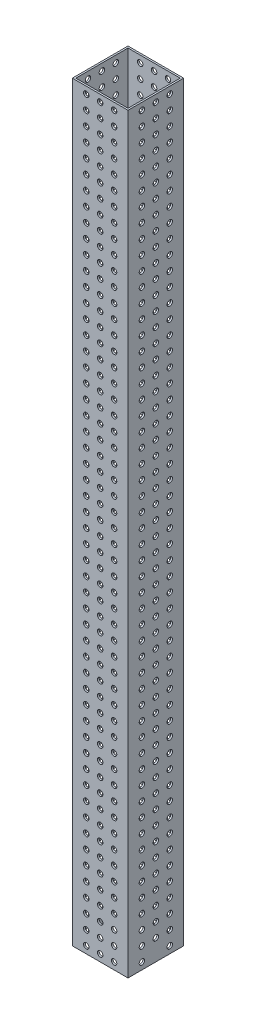
SolidWorks part; units mm, degrees
ref_plane "Front Plane" through (0, 0, 0) normal (0, 0, 1) x (1, 0, 0)
ref_plane "Top Plane" through (0, 0, 0) normal (0, 1, 0) x (1, 0, 0)
ref_plane "Right Plane" through (0, 0, 0) normal (1, 0, 0) x (0, 0, -1)
sketch "Sketch1" plane through (0, 0, 0) normal (0, 1, 0) x (1, 0, 0)
  line L1 (-25.4, 25.4) -> (25.4, 25.4)
  line L2 (-25.4, 25.4) -> (-25.4, -25.4)
  line L3 (-25.4, -25.4) -> (25.4, -25.4)
  line L4 (25.4, 25.4) -> (25.4, -25.4)
  line L5 (-25.4, 25.4) -> (25.4, -25.4) construction
  line L6 (-25.4, -25.4) -> (25.4, 25.4) construction
  line L7 (23.8125, 23.8125) -> (-23.8125, 23.8125)
  line L8 (23.8125, 23.8125) -> (23.8125, -23.8125)
  line L9 (23.8125, -23.8125) -> (-23.8125, -23.8125)
  line L10 (-23.8125, 23.8125) -> (-23.8125, -23.8125)
  line L11 (23.8125, 23.8125) -> (-23.8125, -23.8125) construction
  line L12 (23.8125, -23.8125) -> (-23.8125, 23.8125) construction
  point P0 (0, 0)
  point P6 (0, 0)
  dimension "D1" = 50.8
  dimension "D2" = 50.8
  dimension "D3" = 1.5875
  dimension "D4" = 1.5875
extrude "Boss-Extrude1" add sketch "Sketch1" along normal blind 685.8
sketch "Sketch2" plane through (0, 0, 25.4) normal (0, 0, 1) x (1, 0, 0)
  line L0 (0, 685.8) -> (0, 0) construction
  line L1 (-25.4, 685.8) -> (25.4, 685.8) construction
  line L2 (-25.4, 685.8) -> (-25.4, 0) construction
  line L3 (-6.35, -314.2) -> (-6.35, 49685.8) construction
  circle A0 centre (-12.7, 679.45) radius 2.4892
  circle A1 centre (-12.7, 666.75) radius 2.4892
  circle A2 centre (-12.7, 654.05) radius 2.4892
  circle A3 centre (-12.7, 641.35) radius 2.4892
  circle A4 centre (-12.7, 628.65) radius 2.4892
  circle A5 centre (-12.7, 615.95) radius 2.4892
  circle A6 centre (-12.7, 603.25) radius 2.4892
  circle A7 centre (-12.7, 590.55) radius 2.4892
  circle A8 centre (-12.7, 577.85) radius 2.4892
  circle A9 centre (-12.7, 565.15) radius 2.4892
  circle A10 centre (-12.7, 552.45) radius 2.4892
  circle A11 centre (-12.7, 539.75) radius 2.4892
  circle A12 centre (-12.7, 527.05) radius 2.4892
  circle A13 centre (-12.7, 514.35) radius 2.4892
  circle A14 centre (-12.7, 501.65) radius 2.4892
  circle A15 centre (-12.7, 488.95) radius 2.4892
  circle A16 centre (-12.7, 476.25) radius 2.4892
  circle A17 centre (-12.7, 463.55) radius 2.4892
  circle A18 centre (-12.7, 450.85) radius 2.4892
  circle A19 centre (-12.7, 438.15) radius 2.4892
  circle A20 centre (-12.7, 425.45) radius 2.4892
  circle A21 centre (-12.7, 412.75) radius 2.4892
  circle A22 centre (-12.7, 400.05) radius 2.4892
  circle A23 centre (-12.7, 387.35) radius 2.4892
  circle A24 centre (-12.7, 374.65) radius 2.4892
  circle A25 centre (-12.7, 361.95) radius 2.4892
  circle A26 centre (-12.7, 349.25) radius 2.4892
  circle A27 centre (-12.7, 336.55) radius 2.4892
  circle A28 centre (-12.7, 323.85) radius 2.4892
  circle A29 centre (-12.7, 311.15) radius 2.4892
  circle A30 centre (-12.7, 298.45) radius 2.4892
  circle A31 centre (-12.7, 285.75) radius 2.4892
  circle A32 centre (-12.7, 273.05) radius 2.4892
  circle A33 centre (-12.7, 260.35) radius 2.4892
  circle A34 centre (-12.7, 247.65) radius 2.4892
  circle A35 centre (-12.7, 234.95) radius 2.4892
  circle A36 centre (-12.7, 222.25) radius 2.4892
  circle A37 centre (-12.7, 209.55) radius 2.4892
  circle A38 centre (-12.7, 196.85) radius 2.4892
  circle A39 centre (-12.7, 184.15) radius 2.4892
  circle A40 centre (-12.7, 171.45) radius 2.4892
  circle A41 centre (-12.7, 158.75) radius 2.4892
  circle A42 centre (-12.7, 146.05) radius 2.4892
  circle A43 centre (-12.7, 133.35) radius 2.4892
  circle A44 centre (-12.7, 120.65) radius 2.4892
  circle A45 centre (-12.7, 107.95) radius 2.4892
  circle A46 centre (-12.7, 95.25) radius 2.4892
  circle A47 centre (-12.7, 82.55) radius 2.4892
  circle A48 centre (-12.7, 69.85) radius 2.4892
  circle A49 centre (-12.7, 57.15) radius 2.4892
  circle A50 centre (-12.7, 44.45) radius 2.4892
  circle A51 centre (-12.7, 31.75) radius 2.4892
  circle A52 centre (-12.7, 19.05) radius 2.4892
  circle A53 centre (-12.7, 6.35) radius 2.4892
  circle A54 centre (12.7, 6.35) radius 2.4892
  circle A55 centre (12.7, 19.05) radius 2.4892
  circle A56 centre (12.7, 31.75) radius 2.4892
  circle A57 centre (12.7, 44.45) radius 2.4892
  circle A58 centre (12.7, 57.15) radius 2.4892
  circle A59 centre (12.7, 69.85) radius 2.4892
  circle A60 centre (12.7, 82.55) radius 2.4892
  circle A61 centre (12.7, 95.25) radius 2.4892
  circle A62 centre (12.7, 107.95) radius 2.4892
  circle A63 centre (12.7, 120.65) radius 2.4892
  circle A64 centre (12.7, 133.35) radius 2.4892
  circle A65 centre (12.7, 146.05) radius 2.4892
  circle A66 centre (12.7, 158.75) radius 2.4892
  circle A67 centre (12.7, 171.45) radius 2.4892
  circle A68 centre (12.7, 184.15) radius 2.4892
  circle A69 centre (12.7, 196.85) radius 2.4892
  circle A70 centre (12.7, 209.55) radius 2.4892
  circle A71 centre (12.7, 222.25) radius 2.4892
  circle A72 centre (12.7, 234.95) radius 2.4892
  circle A73 centre (12.7, 247.65) radius 2.4892
  circle A74 centre (12.7, 260.35) radius 2.4892
  circle A75 centre (12.7, 273.05) radius 2.4892
  circle A76 centre (12.7, 285.75) radius 2.4892
  circle A77 centre (12.7, 298.45) radius 2.4892
  circle A78 centre (12.7, 311.15) radius 2.4892
  circle A79 centre (12.7, 323.85) radius 2.4892
  circle A80 centre (12.7, 336.55) radius 2.4892
  circle A81 centre (12.7, 374.65) radius 2.4892
  circle A82 centre (12.7, 361.95) radius 2.4892
  circle A83 centre (12.7, 349.25) radius 2.4892
  circle A84 centre (12.7, 387.35) radius 2.4892
  circle A85 centre (12.7, 400.05) radius 2.4892
  circle A86 centre (12.7, 412.75) radius 2.4892
  circle A87 centre (12.7, 425.45) radius 2.4892
  circle A88 centre (12.7, 438.15) radius 2.4892
  circle A89 centre (12.7, 450.85) radius 2.4892
  circle A90 centre (12.7, 463.55) radius 2.4892
  circle A91 centre (12.7, 476.25) radius 2.4892
  circle A92 centre (12.7, 488.95) radius 2.4892
  circle A93 centre (12.7, 501.65) radius 2.4892
  circle A94 centre (12.7, 514.35) radius 2.4892
  circle A95 centre (12.7, 527.05) radius 2.4892
  circle A96 centre (12.7, 539.75) radius 2.4892
  circle A97 centre (12.7, 552.45) radius 2.4892
  circle A98 centre (12.7, 565.15) radius 2.4892
  circle A99 centre (12.7, 577.85) radius 2.4892
  circle A100 centre (12.7, 590.55) radius 2.4892
  circle A101 centre (12.7, 603.25) radius 2.4892
  circle A102 centre (12.7, 615.95) radius 2.4892
  circle A103 centre (12.7, 628.65) radius 2.4892
  circle A104 centre (12.7, 641.35) radius 2.4892
  circle A105 centre (12.7, 654.05) radius 2.4892
  circle A106 centre (12.7, 666.75) radius 2.4892
  circle A107 centre (12.7, 679.45) radius 2.4892
  circle A108 centre (0, 6.35) radius 2.4892
  circle A109 centre (0, 19.05) radius 2.4892
  circle A110 centre (0, 31.75) radius 2.4892
  circle A111 centre (0, 44.45) radius 2.4892
  circle A112 centre (0, 57.15) radius 2.4892
  circle A113 centre (0, 69.85) radius 2.4892
  circle A114 centre (0, 82.55) radius 2.4892
  circle A115 centre (0, 95.25) radius 2.4892
  circle A116 centre (0, 107.95) radius 2.4892
  circle A117 centre (0, 120.65) radius 2.4892
  circle A118 centre (0, 133.35) radius 2.4892
  circle A119 centre (0, 146.05) radius 2.4892
  circle A120 centre (0, 158.75) radius 2.4892
  circle A121 centre (0, 171.45) radius 2.4892
  circle A122 centre (0, 184.15) radius 2.4892
  circle A123 centre (0, 196.85) radius 2.4892
  circle A124 centre (0, 209.55) radius 2.4892
  circle A125 centre (0, 222.25) radius 2.4892
  circle A126 centre (0, 234.95) radius 2.4892
  circle A127 centre (0, 247.65) radius 2.4892
  circle A128 centre (0, 260.35) radius 2.4892
  circle A129 centre (0, 273.05) radius 2.4892
  circle A130 centre (0, 285.75) radius 2.4892
  circle A131 centre (0, 298.45) radius 2.4892
  circle A132 centre (0, 311.15) radius 2.4892
  circle A133 centre (0, 323.85) radius 2.4892
  circle A134 centre (0, 336.55) radius 2.4892
  circle A135 centre (0, 349.25) radius 2.4892
  circle A136 centre (0, 361.95) radius 2.4892
  circle A137 centre (0, 374.65) radius 2.4892
  circle A138 centre (0, 387.35) radius 2.4892
  circle A139 centre (0, 400.05) radius 2.4892
  circle A140 centre (0, 412.75) radius 2.4892
  circle A141 centre (0, 425.45) radius 2.4892
  circle A142 centre (0, 438.15) radius 2.4892
  circle A143 centre (0, 450.85) radius 2.4892
  circle A144 centre (0, 463.55) radius 2.4892
  circle A145 centre (0, 476.25) radius 2.4892
  circle A146 centre (0, 488.95) radius 2.4892
  circle A147 centre (0, 501.65) radius 2.4892
  circle A148 centre (0, 514.35) radius 2.4892
  circle A149 centre (0, 527.05) radius 2.4892
  circle A150 centre (0, 539.75) radius 2.4892
  circle A151 centre (0, 552.45) radius 2.4892
  circle A152 centre (0, 565.15) radius 2.4892
  circle A153 centre (0, 577.85) radius 2.4892
  circle A154 centre (0, 590.55) radius 2.4892
  circle A155 centre (0, 603.25) radius 2.4892
  circle A156 centre (0, 615.95) radius 2.4892
  circle A157 centre (0, 628.65) radius 2.4892
  circle A158 centre (0, 641.35) radius 2.4892
  circle A159 centre (0, 654.05) radius 2.4892
  circle A160 centre (0, 666.75) radius 2.4892
  circle A161 centre (0, 679.45) radius 2.4892
  dimension "D1" = 4.9784
  dimension "D2" = 6.35
  dimension "D3" = 12.7
  dimension "D5" = 12.7
  dimension "D6" = 6.35
  dimension "D4" = 54
extrude "Cut-Extrude1" cut sketch "Sketch2" against normal through all
sketch "Sketch4" plane through (25.4, 0, 0) normal (1, 0, 0) x (0, 0, -1)
  line L0 (0, 685.8) -> (0, 0) construction
  line L1 (-25.4, 685.8) -> (25.4, 685.8) construction
  line L2 (-25.4, 685.8) -> (-25.4, 0) construction
  line L3 (-6.35, -314.2) -> (-6.35, 49685.8) construction
  circle A0 centre (-12.7, 679.45) radius 2.4892
  circle A1 centre (-12.7, 666.75) radius 2.4892
  circle A2 centre (-12.7, 654.05) radius 2.4892
  circle A3 centre (-12.7, 641.35) radius 2.4892
  circle A4 centre (-12.7, 628.65) radius 2.4892
  circle A5 centre (-12.7, 615.95) radius 2.4892
  circle A6 centre (-12.7, 603.25) radius 2.4892
  circle A7 centre (-12.7, 590.55) radius 2.4892
  circle A8 centre (-12.7, 577.85) radius 2.4892
  circle A9 centre (-12.7, 565.15) radius 2.4892
  circle A10 centre (-12.7, 552.45) radius 2.4892
  circle A11 centre (-12.7, 539.75) radius 2.4892
  circle A12 centre (-12.7, 527.05) radius 2.4892
  circle A13 centre (-12.7, 514.35) radius 2.4892
  circle A14 centre (-12.7, 501.65) radius 2.4892
  circle A15 centre (-12.7, 488.95) radius 2.4892
  circle A16 centre (-12.7, 476.25) radius 2.4892
  circle A17 centre (-12.7, 463.55) radius 2.4892
  circle A18 centre (-12.7, 450.85) radius 2.4892
  circle A19 centre (-12.7, 438.15) radius 2.4892
  circle A20 centre (-12.7, 425.45) radius 2.4892
  circle A21 centre (-12.7, 412.75) radius 2.4892
  circle A22 centre (-12.7, 400.05) radius 2.4892
  circle A23 centre (-12.7, 387.35) radius 2.4892
  circle A24 centre (-12.7, 374.65) radius 2.4892
  circle A25 centre (-12.7, 361.95) radius 2.4892
  circle A26 centre (-12.7, 349.25) radius 2.4892
  circle A27 centre (-12.7, 336.55) radius 2.4892
  circle A28 centre (-12.7, 323.85) radius 2.4892
  circle A29 centre (-12.7, 311.15) radius 2.4892
  circle A30 centre (-12.7, 298.45) radius 2.4892
  circle A31 centre (-12.7, 285.75) radius 2.4892
  circle A32 centre (-12.7, 273.05) radius 2.4892
  circle A33 centre (-12.7, 260.35) radius 2.4892
  circle A34 centre (-12.7, 247.65) radius 2.4892
  circle A35 centre (-12.7, 234.95) radius 2.4892
  circle A36 centre (-12.7, 222.25) radius 2.4892
  circle A37 centre (-12.7, 209.55) radius 2.4892
  circle A38 centre (-12.7, 196.85) radius 2.4892
  circle A39 centre (-12.7, 184.15) radius 2.4892
  circle A40 centre (-12.7, 171.45) radius 2.4892
  circle A41 centre (-12.7, 158.75) radius 2.4892
  circle A42 centre (-12.7, 146.05) radius 2.4892
  circle A43 centre (-12.7, 133.35) radius 2.4892
  circle A44 centre (-12.7, 120.65) radius 2.4892
  circle A45 centre (-12.7, 107.95) radius 2.4892
  circle A46 centre (-12.7, 95.25) radius 2.4892
  circle A47 centre (-12.7, 82.55) radius 2.4892
  circle A48 centre (-12.7, 69.85) radius 2.4892
  circle A49 centre (-12.7, 57.15) radius 2.4892
  circle A50 centre (-12.7, 44.45) radius 2.4892
  circle A51 centre (-12.7, 31.75) radius 2.4892
  circle A52 centre (-12.7, 19.05) radius 2.4892
  circle A53 centre (-12.7, 6.35) radius 2.4892
  circle A54 centre (12.7, 273.05) radius 2.4892
  circle A55 centre (12.7, 285.75) radius 2.4892
  circle A56 centre (12.7, 298.45) radius 2.4892
  circle A57 centre (12.7, 311.15) radius 2.4892
  circle A58 centre (12.7, 323.85) radius 2.4892
  circle A59 centre (12.7, 336.55) radius 2.4892
  circle A60 centre (12.7, 349.25) radius 2.4892
  circle A61 centre (12.7, 361.95) radius 2.4892
  circle A62 centre (12.7, 374.65) radius 2.4892
  circle A63 centre (12.7, 387.35) radius 2.4892
  circle A64 centre (12.7, 400.05) radius 2.4892
  circle A65 centre (12.7, 412.75) radius 2.4892
  circle A66 centre (12.7, 425.45) radius 2.4892
  circle A67 centre (12.7, 438.15) radius 2.4892
  circle A68 centre (12.7, 450.85) radius 2.4892
  circle A69 centre (12.7, 463.55) radius 2.4892
  circle A70 centre (12.7, 476.25) radius 2.4892
  circle A71 centre (12.7, 488.95) radius 2.4892
  circle A72 centre (12.7, 501.65) radius 2.4892
  circle A73 centre (12.7, 514.35) radius 2.4892
  circle A74 centre (12.7, 527.05) radius 2.4892
  circle A75 centre (12.7, 539.75) radius 2.4892
  circle A76 centre (12.7, 552.45) radius 2.4892
  circle A77 centre (12.7, 565.15) radius 2.4892
  circle A78 centre (12.7, 577.85) radius 2.4892
  circle A79 centre (12.7, 590.55) radius 2.4892
  circle A80 centre (12.7, 603.25) radius 2.4892
  circle A81 centre (12.7, 615.95) radius 2.4892
  circle A82 centre (12.7, 628.65) radius 2.4892
  circle A83 centre (12.7, 641.35) radius 2.4892
  circle A84 centre (12.7, 654.05) radius 2.4892
  circle A85 centre (12.7, 666.75) radius 2.4892
  circle A86 centre (12.7, 19.05) radius 2.4892
  circle A87 centre (12.7, 31.75) radius 2.4892
  circle A88 centre (12.7, 44.45) radius 2.4892
  circle A89 centre (12.7, 57.15) radius 2.4892
  circle A90 centre (12.7, 69.85) radius 2.4892
  circle A91 centre (12.7, 82.55) radius 2.4892
  circle A92 centre (12.7, 95.25) radius 2.4892
  circle A93 centre (12.7, 107.95) radius 2.4892
  circle A94 centre (12.7, 120.65) radius 2.4892
  circle A95 centre (12.7, 133.35) radius 2.4892
  circle A96 centre (12.7, 146.05) radius 2.4892
  circle A97 centre (12.7, 158.75) radius 2.4892
  circle A98 centre (12.7, 171.45) radius 2.4892
  circle A99 centre (12.7, 184.15) radius 2.4892
  circle A100 centre (12.7, 196.85) radius 2.4892
  circle A101 centre (12.7, 209.55) radius 2.4892
  circle A102 centre (12.7, 222.25) radius 2.4892
  circle A103 centre (12.7, 234.95) radius 2.4892
  circle A104 centre (12.7, 247.65) radius 2.4892
  circle A105 centre (12.7, 260.35) radius 2.4892
  circle A106 centre (12.7, 6.35) radius 2.4892
  circle A107 centre (12.7, 679.45) radius 2.4892
  circle A108 centre (0, 82.55) radius 2.4892
  circle A109 centre (0, 19.05) radius 2.4892
  circle A110 centre (0, 31.75) radius 2.4892
  circle A111 centre (0, 44.45) radius 2.4892
  circle A112 centre (0, 57.15) radius 2.4892
  circle A113 centre (0, 69.85) radius 2.4892
  circle A114 centre (0, 95.25) radius 2.4892
  circle A115 centre (0, 107.95) radius 2.4892
  circle A116 centre (0, 120.65) radius 2.4892
  circle A117 centre (0, 133.35) radius 2.4892
  circle A118 centre (0, 146.05) radius 2.4892
  circle A119 centre (0, 158.75) radius 2.4892
  circle A120 centre (0, 171.45) radius 2.4892
  circle A121 centre (0, 184.15) radius 2.4892
  circle A122 centre (0, 196.85) radius 2.4892
  circle A123 centre (0, 209.55) radius 2.4892
  circle A124 centre (0, 222.25) radius 2.4892
  circle A125 centre (0, 234.95) radius 2.4892
  circle A126 centre (0, 247.65) radius 2.4892
  circle A127 centre (0, 260.35) radius 2.4892
  circle A128 centre (0, 273.05) radius 2.4892
  circle A129 centre (0, 285.75) radius 2.4892
  circle A130 centre (0, 298.45) radius 2.4892
  circle A131 centre (0, 311.15) radius 2.4892
  circle A132 centre (0, 323.85) radius 2.4892
  circle A133 centre (0, 336.55) radius 2.4892
  circle A134 centre (0, 361.95) radius 2.4892
  circle A135 centre (0, 374.65) radius 2.4892
  circle A136 centre (0, 387.35) radius 2.4892
  circle A137 centre (0, 400.05) radius 2.4892
  circle A138 centre (0, 412.75) radius 2.4892
  circle A139 centre (0, 425.45) radius 2.4892
  circle A140 centre (0, 438.15) radius 2.4892
  circle A141 centre (0, 450.85) radius 2.4892
  circle A142 centre (0, 463.55) radius 2.4892
  circle A143 centre (0, 476.25) radius 2.4892
  circle A144 centre (0, 488.95) radius 2.4892
  circle A145 centre (0, 501.65) radius 2.4892
  circle A146 centre (0, 514.35) radius 2.4892
  circle A147 centre (0, 527.05) radius 2.4892
  circle A148 centre (0, 539.75) radius 2.4892
  circle A149 centre (0, 552.45) radius 2.4892
  circle A150 centre (0, 565.15) radius 2.4892
  circle A151 centre (0, 577.85) radius 2.4892
  circle A152 centre (0, 590.55) radius 2.4892
  circle A153 centre (0, 603.25) radius 2.4892
  circle A154 centre (0, 615.95) radius 2.4892
  circle A155 centre (0, 628.65) radius 2.4892
  circle A156 centre (0, 641.35) radius 2.4892
  circle A157 centre (0, 654.05) radius 2.4892
  circle A158 centre (0, 666.75) radius 2.4892
  circle A159 centre (0, 679.45) radius 2.4892
  circle A160 centre (0, 349.25) radius 2.4892
  dimension "D1" = 4.9784
  dimension "D2" = 12.7
  dimension "D3" = 6.35
  dimension "D5" = 12.7
  dimension "D6" = 6.35
  dimension "D4" = 54
extrude "Cut-Extrude2" cut sketch "Sketch4" against normal through all
